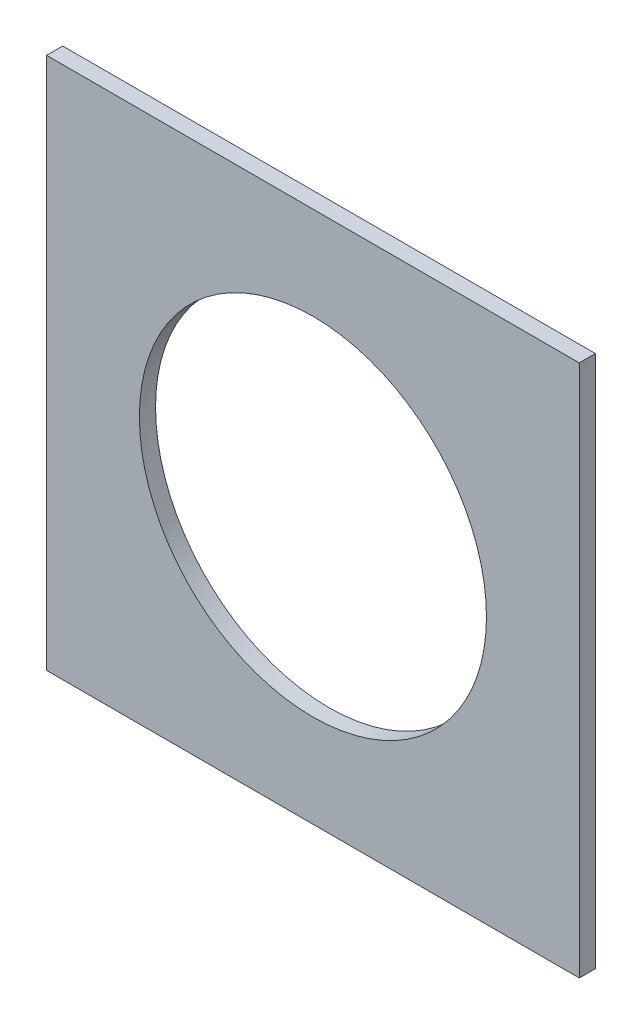
SolidWorks part; units mm, degrees
ref_plane "Front Plane" through (0, 0, 0) normal (0, 0, 1) x (1, 0, 0)
ref_plane "Top Plane" through (0, 0, 0) normal (0, 1, 0) x (1, 0, 0)
ref_plane "Right Plane" through (0, 0, 0) normal (1, 0, 0) x (0, 0, -1)
sketch "Sketch1" plane through (0, 0, 0) normal (0, 0, 1) x (1, 0, 0)
  line L1 (-165, -165) -> (165, -165)
  line L2 (-165, -165) -> (-165, 165)
  line L3 (-165, 165) -> (165, 165)
  line L4 (165, -165) -> (165, 165)
  line L5 (-165, -165) -> (165, 165) construction
  line L6 (-165, 165) -> (165, -165) construction
  point P0 (0, 0)
  dimension "D1" = 330
  dimension "D2" = 330
extrude "Boss-Extrude1" add sketch "Sketch1" against normal blind 10
sketch "Sketch2" plane through (0, 0, 0) normal (0, 0, 1) x (1, 0, 0)
  circle A0 centre (0, 0) radius 107.5
extrude "Cut-Extrude1" cut sketch "Sketch2" against normal blind 10
